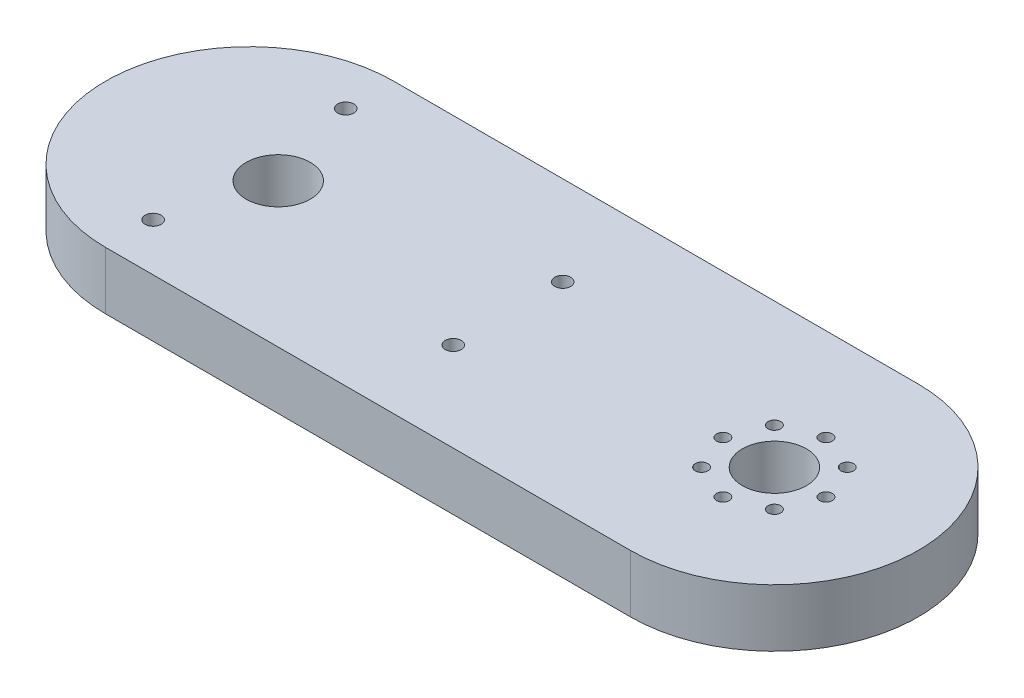
SolidWorks part; units mm, degrees
ref_plane "Front Plane" through (0, 0, 0) normal (0, 0, 1) x (1, 0, 0)
ref_plane "Top Plane" through (0, 0, 0) normal (0, 1, 0) x (1, 0, 0)
ref_plane "Right Plane" through (0, 0, 0) normal (1, 0, 0) x (0, 0, -1)
sketch "Sketch2" plane through (0, 0, 0) normal (0, 1, 0) x (1, 0, 0)
  line L0 (41, 0) -> (-41, 0) construction
  line L1 (41, -22.5) -> (-41, -22.5)
  line L2 (41, 22.5) -> (-41, 22.5)
  arc A0 (41, -22.5) -> (41, 22.5) centre (41, 0) ccw
  arc A1 (-41, 22.5) -> (-41, -22.5) centre (-41, 0) ccw
  point P2 (0, 0)
  dimension "D2" = 82
  dimension "D1" = 45
extrude "Boss-Extrude1" add sketch "Sketch2" along normal mid plane 9
sketch "Sketch3" plane through (0, 4.5, 0) normal (0, 1, 0) x (1, 0, 0)
  circle A0 centre (46.6922, 5.6922) radius 0.99
  circle A1 centre (41, 0) radius 3.5007 construction
  arc A2 (41, -22.5) -> (41, 22.5) centre (41, 0) ccw construction
  circle A3 centre (41, 8.05) radius 0.99
  circle A4 centre (49.05, 0) radius 0.99
  circle A5 centre (46.6922, -5.6922) radius 0.99
  circle A6 centre (41, -8.05) radius 0.99
  circle A7 centre (35.3078, -5.6922) radius 0.99
  circle A8 centre (32.95, 0) radius 0.99
  circle A9 centre (35.3078, 5.6922) radius 0.99
  dimension "D2" = 1.98
  dimension "D1" = 8.05
  dimension "D3" = 8
extrude "Cut-Extrude1" cut sketch "Sketch3" against normal through all both and the other way through all
sketch "Sketch4" plane through (0, 4.5, 0) normal (0, 1, 0) x (1, 0, 0)
  circle A0 centre (41, 0) radius 5
  arc A1 (41, -22.5) -> (41, 22.5) centre (41, 0) ccw construction
  dimension "D1" = 10
extrude "Cut-Extrude2" cut sketch "Sketch4" against normal through all
sketch "Sketch5" plane through (0, 4.5, 0) normal (0, 1, 0) x (1, 0, 0)
  line L0 (0, 0) -> (-45.6257, 0) construction
  circle A0 centre (-41.025, -15.05) radius 1.25
  circle A1 centre (-41.025, 15.05) radius 1.25
  circle A2 centre (-0.625, 8.55) radius 1.25
  circle A3 centre (-0.625, -8.55) radius 1.25
  circle A4 centre (-36.525, 0) radius 5
  dimension "D1" = 2.5
  dimension "D4" = 2.5
  dimension "D5" = 2.5
  dimension "D8" = 10
  dimension "D2" = 15.05
  dimension "D3" = 15.05
  dimension "D6" = 8.55
  dimension "D7" = 40.4
  dimension "D9" = 4.5
extrude "Cut-Extrude3" cut sketch "Sketch5" against normal through all both and the other way through all
